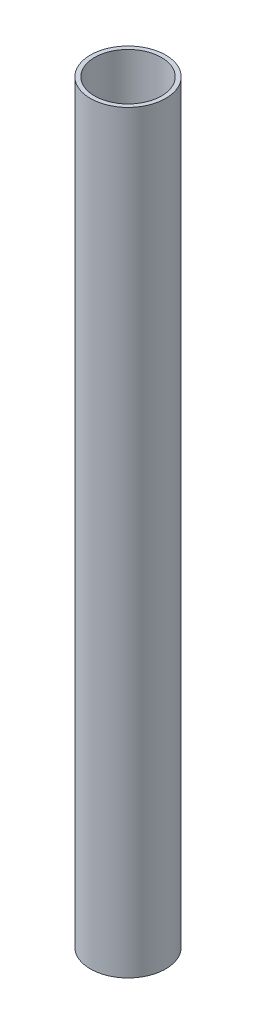
SolidWorks part; units mm, degrees
material "AISI 1020"
ref_plane "Front Plane" through (0, 0, 0) normal (0, 0, 1) x (1, 0, 0)
ref_plane "Top Plane" through (0, 0, 0) normal (0, 1, 0) x (1, 0, 0)
ref_plane "Right Plane" through (0, 0, 0) normal (1, 0, 0) x (0, 0, -1)
sketch "Sketch1" plane through (0, 0, 0) normal (0, 1, 0) x (1, 0, 0)
  circle A0 centre (0, 0) radius 7.0485
  circle A1 centre (0, 0) radius 7.9375
  dimension "D1" = 14.097
  dimension "D2" = 15.875
extrude "Boss-Extrude1" add sketch "Sketch1" along normal blind 159
